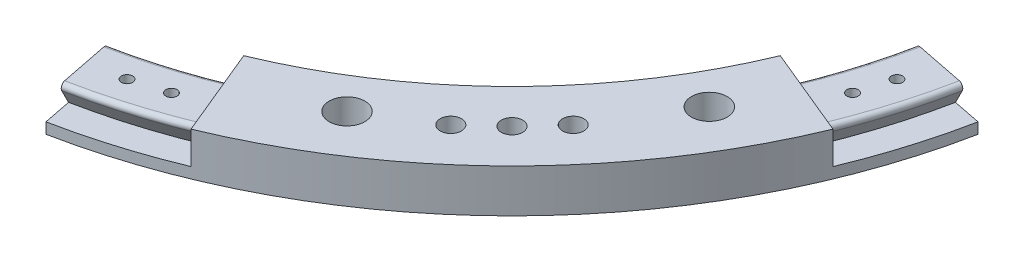
SolidWorks part; units mm, degrees
material "ABS PC"
ref_plane "Front Plane" through (0, 0, 0) normal (0, 0, 1) x (1, 0, 0)
ref_plane "Top Plane" through (0, 0, 0) normal (0, 1, 0) x (1, 0, 0)
ref_plane "Right Plane" through (0, 0, 0) normal (1, 0, 0) x (0, 0, -1)
sketch "Sketch1" plane through (0, 0, 0) normal (0, 0, 1) x (1, 0, 0)
  line L0 (0, 1125.8152) -> (0, -48874.1848) construction
  line L1 (145.5262, 1052.195) -> (152.4, 1052.195)
  line L9 (145.5262, 1064.895) -> (174.1012, 1064.895)
  line L10 (145.5262, 1064.895) -> (145.5262, 1052.195)
  line L11 (145.5262, 1052.195) -> (174.1012, 1052.195)
  line L12 (174.1012, 1064.895) -> (174.1012, 1052.195)
revolve "Revolve1" add sketch "Sketch1" angle 360 about L0
sketch "Sketch19" plane through (0, 1064.895, 0) normal (0, 1, 0) x (1, 0, 0)
  line L0 (160.8486, -66.6257) -> (134.4487, -55.6905)
  line L1 (160.8486, 66.6257) -> (134.4487, 55.6905)
  line L2 (-66.6257, 160.8486) -> (-55.6905, 134.4487)
  line L3 (66.6257, 160.8486) -> (55.6905, 134.4487)
  line L4 (0, 174.1012) -> (0, -174.1012) construction
  line L5 (174.1012, 0) -> (-174.1012, 0) construction
  line L6 (-134.4487, -55.6905) -> (-160.8486, -66.6257)
  line L7 (-55.6905, -134.4487) -> (-66.6257, -160.8486)
  line L8 (55.6905, -134.4487) -> (66.6257, -160.8486)
  line L9 (-134.4487, 55.6905) -> (-160.8486, 66.6257)
  circle A0 centre (0, 0) radius 145.5262 construction
  circle A1 centre (0, 0) radius 174.1012
  arc A2 (-160.8486, 66.6257) -> (-160.8486, -66.6257) centre (0, 0) ccw
  arc A3 (-134.4487, 55.6905) -> (-134.4487, -55.6905) centre (0, 0) ccw
  arc A4 (66.6257, 160.8486) -> (-66.6257, 160.8486) centre (0, 0) ccw
  arc A5 (55.6905, 134.4487) -> (-55.6905, 134.4487) centre (0, 0) ccw
  arc A6 (160.8486, -66.6257) -> (160.8486, 66.6257) centre (0, 0) ccw
  arc A7 (134.4487, -55.6905) -> (134.4487, 55.6905) centre (0, 0) ccw
  arc A8 (-55.6905, -134.4487) -> (55.6905, -134.4487) centre (0, 0) ccw
  arc A9 (-66.6257, -160.8486) -> (66.6257, -160.8486) centre (0, 0) ccw
  dimension "D1" = 22.5
  dimension "D2" = 22.5
  dimension "D3" = 22.5
  dimension "D4" = 22.5
  dimension "D5" = 0
extrude "Cut-Extrude1" cut sketch "Sketch19" against normal blind 9.525
sketch "Sketch21" plane through (0, 0, 0) normal (0, 0, 1) x (1, 0, 0)
  line L0 (-145.5262, 1055.37) -> (-174.1012, 1055.37)
  line L1 (-145.5262, 1055.37) -> (-174.1012, 1055.37)
  line L2 (-165.6726, 1055.37) -> (-169.3387, 1061.72)
  line L3 (-169.3387, 1061.72) -> (-150.2887, 1061.72)
  line L4 (-150.2887, 1061.72) -> (-153.9549, 1055.37)
  line L5 (-159.8137, 1055.37) -> (-159.8137, 1061.72) construction
  line L6 (0, 0) -> (0, 1055.37) construction
  line L7 (55.6905, 1055.37) -> (-55.6905, 1055.37) construction
  dimension "D1" = 30
  dimension "D2" = 6.35
  dimension "D3" = 19.05
revolve "Revolve2" add sketch "Sketch21" angle 360 about L6
hole_wizard "#12 Clearance Hole1" positions "Sketch9" profile "Sketch10" hole size "#12" standard "ANSI Inch" end condition through all
sketch "Sketch9" plane through (0, 1052.195, 0) normal (0, -1, 0) x (-1, 0, 0)
  line L0 (0, 0) -> (113.0054, 113.0054) construction
  line L3 (0, 0) -> (103.6677, 121.6282) construction
  arc A0 (103.6677, 121.6282) -> (121.6282, 103.6677) centre (0, 0) cw
  circle A1 centre (0, 0) radius 159.8137 construction
  point P0 (103.6677, 121.6282)
  point P2 (121.6282, 103.6677)
  point P15 (113.0054, 113.0054)
sketch "Sketch10" plane through (-103.6677, 1052.195, -121.6282) normal (1, 0, 0) x (0, 0, -1)
  line L0 (0, 0) -> (0, 12.7)
  line L1 (0, 12.7) -> (3.1242, 12.7)
  line L2 (3.1242, 12.7) -> (3.1242, 0)
  line L5 (3.1242, 0) -> (0, 0)
  line L11 (0, -6.35) -> (0, 107.95) construction
  dimension "Thru Hole Dia." = 6.2484
  dimension "Thru Hole Depth" = 12.7
hole_wizard "M4x0.7 Tapped Hole1" positions "Sketch24" profile "Sketch25" tap size "M4x0.7" standard "ANSI Metric" end condition through all
sketch "Sketch24" plane through (0, 1061.72, 0) normal (0, 1, 0) x (1, 0, 0)
  line L0 (-51.3704, 151.3324) -> (0, 0) construction
  line L1 (0, 0) -> (-41.3628, 154.3682) construction
  line L4 (-66.6257, 160.8486) -> (-55.6905, 134.4487) construction
  line L5 (0, 174.1012) -> (0, 0) construction
  arc A0 (-51.3704, 151.3324) -> (-41.3628, 154.3682) centre (0, 0) cw
  arc A1 (-103.6677, 121.6282) -> (-121.6282, 103.6677) centre (0, 0) ccw construction
  arc A2 (66.6257, 160.8486) -> (-66.6257, 160.8486) centre (0, 0) ccw construction
  arc A3 (51.3704, 151.3324) -> (41.3628, 154.3682) centre (0, 0) ccw
  point P0 (-51.3704, 151.3324)
  point P2 (-41.3628, 154.3682)
  point P35 (51.3704, 151.3324)
  point P36 (41.3628, 154.3682)
  dimension "D1" = 3.75
  dimension "D2" = 3.75
sketch "Sketch25" plane through (-51.3704, 1061.72, -151.3324) normal (1, 0, 0) x (0, 0, 1)
  line L0 (0, 0) -> (0, 9.525)
  line L1 (0, 9.525) -> (1.65, 9.525)
  line L2 (1.65, 9.525) -> (1.65, 0)
  line L5 (1.65, 0) -> (0, 0)
  line L11 (0, -6.35) -> (0, 107.95) construction
  dimension "Thread Major Dia." = 3.3
  dimension "Thru Tap Drill Depth" = 9.525
pattern_circular "CirPattern1" count 4 over 360 about axis through (0, 0, 0) along (0, 1, 0) of "#12 Clearance Hole1", "M4x0.7 Tapped Hole1"
ref_plane "Plane1" through (0, 1058.545, 0) normal (0, 1, 0) x (1, 0, 0)
hole_wizard "M5 Clearance Hole1" [suppressed] positions "Sketch14" profile "Sketch15" hole size "M5" standard "ANSI Metric"
sketch "Sketch14" plane through (0, 1064.895, 0) normal (0, 1, 0) x (1, 0, 0)
  point P9 (157.7975, -38.1)
  point P12 (157.7975, 0)
  point P14 (157.7975, 38.1)
sketch "Sketch15" plane through (157.7975, 1064.895, 38.1) normal (1, 0, 0) x (0, 0, 1)
  line L0 (0, 0) -> (0, 12.7)
  line L1 (0, 12.7) -> (2.9, 12.7)
  line L2 (2.9, 12.7) -> (2.9, 0)
  line L5 (2.9, 0) -> (0, 0)
  line L11 (0, -6.35) -> (0, 107.95) construction
  dimension "Thru Hole Dia." = 5.8
  dimension "Thru Hole Depth" = 12.7
hole_wizard "Z (0.413) Diameter Hole1" positions "Sketch16" profile "Sketch17" hole size "Z" standard "ANSI Inch" end condition through all
sketch "Sketch16" plane through (0, 1064.895, 0) normal (0, 1, 0) x (1, 0, 0)
  line L0 (-137.0279, -79.1131) -> (137.0279, 79.1131) construction
  line L4 (137.0279, -79.1131) -> (-137.0279, 79.1131) construction
  line L6 (0, 0) -> (0, 158.2262) construction
  line L8 (-85.0149, -133.4467) -> (85.0149, 133.4467) construction
  line L11 (-85.0149, 133.4467) -> (85.0149, -133.4467) construction
  circle A0 centre (0, 0) radius 158.2262 construction
  circle A1 centre (0, 0) radius 145.5262 construction
  point P0 (-137.0279, -79.1131)
  point P2 (137.0279, -79.1131)
  point P4 (137.0279, 79.1131)
  point P6 (-137.0279, 79.1131)
  point P37 (-85.0149, 133.4467)
  point P39 (85.0149, 133.4467)
  point P41 (85.0149, -133.4467)
  point P43 (-85.0149, -133.4467)
  dimension "D2" = 12.7
  dimension "D1" = 120
  dimension "D3" = 65
sketch "Sketch17" plane through (-137.0279, 1064.895, 79.1131) normal (1, 0, 0) x (0, 0, 1)
  line L0 (0, 0) -> (0, 12.7)
  line L1 (0, 12.7) -> (5.2451, 12.7)
  line L2 (5.2451, 12.7) -> (5.2451, 0)
  line L5 (5.2451, 0) -> (0, 0)
  line L11 (0, -6.35) -> (0, 107.95) construction
  dimension "Thru Hole Dia." = 10.4902
  dimension "Thru Hole Depth" = 12.7
sketch "Sketch18" plane through (0, 1064.895, 0) normal (0, 1, 0) x (1, 0, 0)
  circle A5 centre (-103.6677, 121.6282) radius 1.5875
  circle A6 centre (-113.0054, 113.0054) radius 1.5875
  circle A7 centre (-121.6282, 103.6677) radius 1.5875
  circle A10 centre (103.6677, 121.6282) radius 1.5875
  circle A11 centre (113.0054, 113.0054) radius 1.5875
  circle A12 centre (121.6282, 103.6677) radius 1.5875
  circle A14 centre (-121.6282, -103.6677) radius 1.5875
  circle A37 centre (-113.0054, -113.0054) radius 1.5875
  circle A38 centre (-103.6677, -121.6282) radius 1.5875
  circle A39 centre (103.6677, -121.6282) radius 1.5875
  circle A40 centre (113.0054, -113.0054) radius 1.5875
  circle A41 centre (121.6282, -103.6677) radius 1.5875
  circle A53 centre (103.6677, 121.6282) radius 3.1242
  circle A54 centre (103.6677, 121.6282) radius 3.1242
  circle A55 centre (113.0054, 113.0054) radius 3.1242
  circle A56 centre (113.0054, 113.0054) radius 3.1242
  circle A57 centre (103.6677, -121.6282) radius 3.1242
  circle A58 centre (103.6677, -121.6282) radius 3.1242
  circle A59 centre (-121.6282, -103.6677) radius 3.1242
  circle A60 centre (-121.6282, -103.6677) radius 3.1242
  circle A61 centre (-103.6677, -121.6282) radius 3.1242
  circle A62 centre (-103.6677, -121.6282) radius 3.1242
  circle A63 centre (-113.0054, -113.0054) radius 3.1242
  circle A64 centre (-113.0054, -113.0054) radius 3.1242
  circle A65 centre (-103.6677, 121.6282) radius 3.1242
  circle A66 centre (-103.6677, 121.6282) radius 3.1242
  circle A67 centre (-121.6282, 103.6677) radius 3.1242
  circle A68 centre (-121.6282, 103.6677) radius 3.1242
  circle A69 centre (-113.0054, 113.0054) radius 3.1242
  circle A70 centre (-113.0054, 113.0054) radius 3.1242
  circle A73 centre (113.0054, -113.0054) radius 3.1242
  circle A74 centre (113.0054, -113.0054) radius 3.1242
  circle A75 centre (121.6282, -103.6677) radius 3.1242
  circle A76 centre (121.6282, -103.6677) radius 3.1242
  circle A77 centre (121.6282, 103.6677) radius 3.1242
  circle A78 centre (121.6282, 103.6677) radius 3.1242
  dimension "D13" = 3.175
  dimension "D14" = 0
  dimension "D15" = 0
  dimension "D16" = 0
  dimension "D17" = 0
  dimension "D18" = 0
  dimension "D19" = 0
  dimension "D20" = 0
  dimension "D21" = 0
  dimension "D22" = 0
  dimension "D24" = 0
  dimension "D25" = 0
  dimension "D26" = 0
extrude "Boss-Extrude1" [suppressed] add sketch "Sketch18" against normal up to surface (12.7 mm away)
fillet "Fillet1" radius 1.27 8 edges at (-150.2887, 1061.72, 0) (-169.3387, 1061.72, 0) (0, 1061.72, -150.2887) (0, 1061.72, -169.3387) (0, 1061.72, 169.3387) (169.3387, 1061.72, 0) (150.2887, 1061.72, 0) (0, 1061.72, 150.2887)
sketch "Sketch23" plane through (0, 1058.545, 0) normal (0, 1, 0) x (1, 0, 0)
  line L0 (-174.1012, 0) -> (174.1012, 0) construction
  line L1 (0, 174.1012) -> (0, -174.1012) construction
  line L2 (33.9655, 170.7559) -> (-33.9655, -170.7559)
  line L3 (-33.9655, 170.7559) -> (33.9655, -170.7559)
  line L4 (-170.7559, -33.9655) -> (170.7559, 33.9655)
  line L5 (-170.7559, 33.9655) -> (170.7559, -33.9655)
  arc A0 (-160.8486, 66.6257) -> (-160.8486, -66.6257) centre (0, 0) ccw construction
  arc A1 (160.8486, -66.6257) -> (160.8486, 66.6257) centre (0, 0) ccw construction
  arc A2 (66.6257, 160.8486) -> (-66.6257, 160.8486) centre (0, 0) ccw construction
  arc A3 (-66.6257, -160.8486) -> (66.6257, -160.8486) centre (0, 0) ccw construction
  circle A4 centre (0, 0) radius 174.1012
  circle A5 centre (0, 0) radius 145.5262
  point P20 (0, 0)
  point P23 (0, 0)
  point P26 (0, 0)
  point P29 (0, 0)
  dimension "D1" = 22.5
  dimension "D2" = 22.5
extrude "Cut-Extrude2" cut sketch "Sketch23" against normal through all both and the other way through all contours A5 L5 A4 L4 | A5 L2 A4 L3 | A5 L5 A4 L4 | A5 L2 A4 L3
